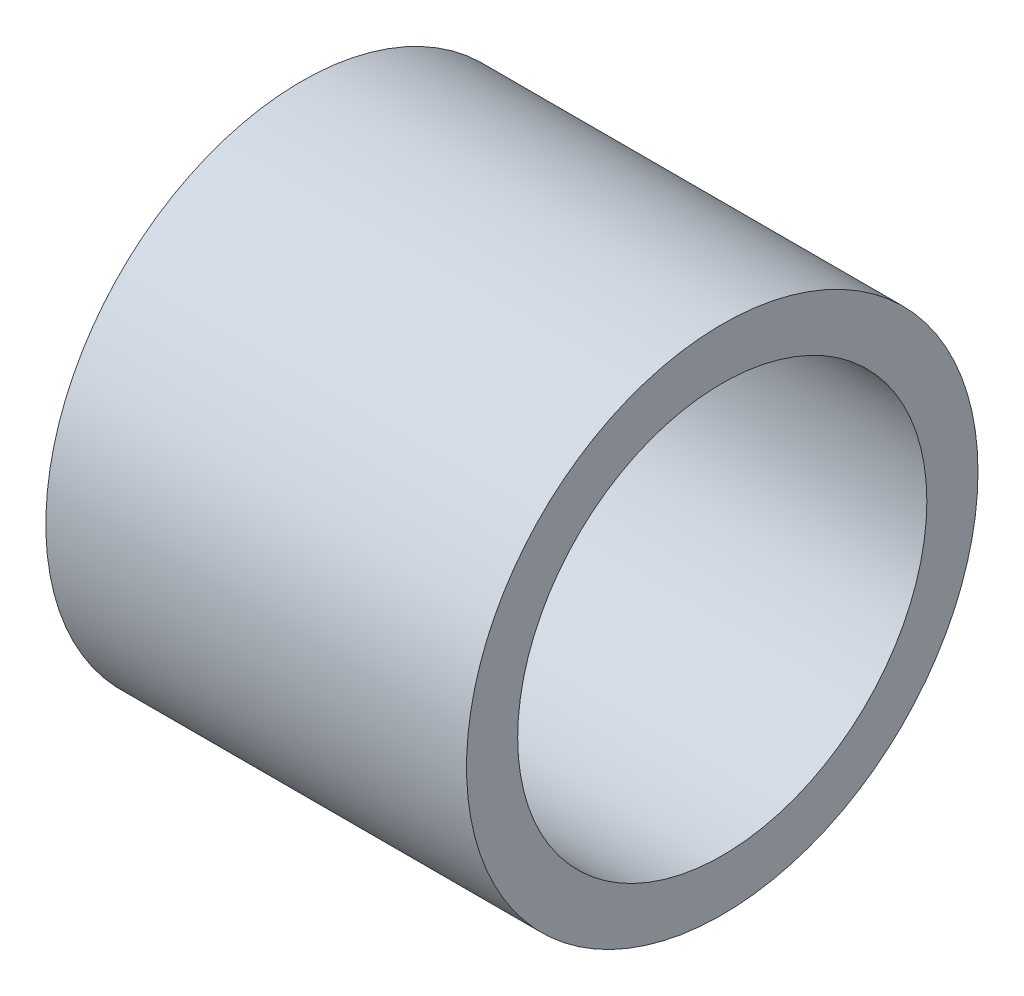
SolidWorks part; units mm, degrees
material "6061-T6 (SS)"
ref_plane "Front Plane" through (0, 0, 0) normal (0, 0, 1) x (1, 0, 0)
ref_plane "Top Plane" through (0, 0, 0) normal (0, 1, 0) x (1, 0, 0)
ref_plane "Right Plane" through (0, 0, 0) normal (1, 0, 0) x (0, 0, -1)
sketch "Sketch1" plane through (0, 0, 0) normal (1, 0, 0) x (0, 0, -1)
  circle A0 centre (0, 0) radius 12.7
  circle A1 centre (0, 0) radius 15.875
  dimension "D1" = 25.4
  dimension "D2" = 3.175
extrude "Extrude1" add sketch "Sketch1" along normal blind 26.115
